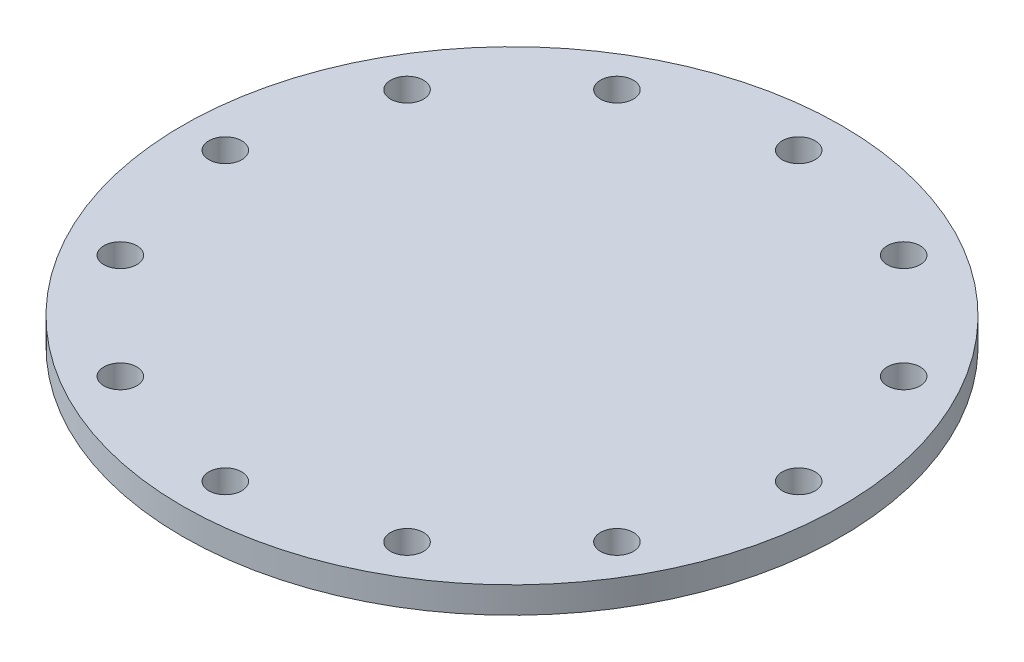
SolidWorks part; units mm, degrees
ref_plane "Front Plane" through (0, 0, 0) normal (0, 0, 1) x (1, 0, 0)
ref_plane "Top Plane" through (0, 0, 0) normal (0, 1, 0) x (1, 0, 0)
ref_plane "Right Plane" through (0, 0, 0) normal (1, 0, 0) x (0, 0, -1)
sketch "Sketch1" plane through (0, 0, 0) normal (0, 1, 0) x (1, 0, 0)
  circle A0 centre (0, 0) radius 250
  dimension "D1" = 500
extrude "Boss-Extrude1" add sketch "Sketch1" along normal blind 20
sketch "Sketch2" plane through (0, 20, 0) normal (0, 1, 0) x (1, 0, 0)
  circle A16 centre (0, 0) radius 217.5 construction
  circle A17 centre (0, 217.5) radius 12.5
  circle A18 centre (108.75, 188.3605) radius 12.5
  circle A19 centre (188.3605, 108.75) radius 12.5
  circle A20 centre (217.5, 0) radius 12.5
  circle A21 centre (188.3605, -108.75) radius 12.5
  circle A22 centre (108.75, -188.3605) radius 12.5
  circle A23 centre (0, -217.5) radius 12.5
  circle A24 centre (-108.75, -188.3605) radius 12.5
  circle A25 centre (-188.3605, -108.75) radius 12.5
  circle A26 centre (-217.5, 0) radius 12.5
  circle A27 centre (-188.3605, 108.75) radius 12.5
  circle A28 centre (-108.75, 188.3605) radius 12.5
  point P4 (0, 0)
  point P29 (1.8383, 0.0078)
  point P31 (0, 0)
  dimension "D2" = 25
  dimension "D1" = 435
  dimension "D3" = 12
sketch "Sketch3" plane through (0, 0, 0) normal (0, 1, 0) x (1, 0, 0)
sketch "Sketch4" plane through (0, 0, 0) normal (0, 1, 0) x (1, 0, 0)
extrude "Cut-Extrude1" cut sketch "Sketch2" against normal blind 20
